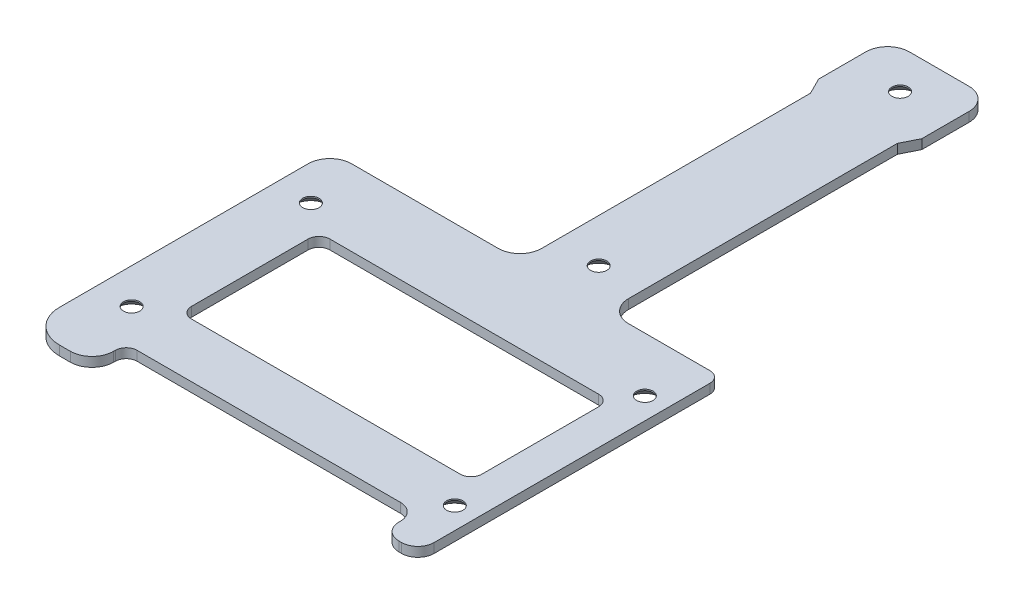
SolidWorks part; units mm, degrees
ref_plane "Front Plane" through (0, 0, 0) normal (0, 0, 1) x (1, 0, 0)
ref_plane "Top Plane" through (0, 0, 0) normal (0, 1, 0) x (1, 0, 0)
ref_plane "Right Plane" through (0, 0, 0) normal (1, 0, 0) x (0, 0, -1)
sketch "Sketch1" plane through (0, 0, 0) normal (0, 1, 0) x (1, 0, 0)
  line L0 (0, 69.2628) -> (0, -31.5647) construction
  line L1 (8, 0) -> (8, 47)
  line L2 (8, 47) -> (9.5, 50)
  line L3 (9.5, 50) -> (9.5, 58.7)
  line L4 (5.5, 62.7) -> (-5.5, 62.7)
  line L5 (20.4805, 0) -> (-4.4805, 0) construction
  line L6 (-8, 0) -> (-8, 47)
  line L7 (-8, 47) -> (-9.5, 50)
  line L8 (-9.5, 50) -> (-9.5, 58.7)
  line L9 (8, 0) -> (8, -2.5)
  line L10 (12, -6.5) -> (27, -6.5)
  line L11 (29, -8.5) -> (29, -56)
  line L12 (19.5, -56) -> (-29, -56)
  line L13 (-43, -56) -> (-43, -10.5)
  line L14 (-39, -6.5) -> (-12, -6.5)
  line L15 (-8, -2.5) -> (-8, 0)
  line L16 (-5.75, -75.9674) -> (-5.75, -4.8448) construction
  line L17 (-36.5, -8.9258) -> (-36.5, -55.9065) construction
  line L18 (25, -8.9258) -> (25, -55.9065) construction
  line L19 (-31, -22.5) -> (-31, -44)
  line L20 (22.5, -22.5) -> (22.5, -44)
  line L21 (-29, -46) -> (20.5, -46)
  line L22 (-29, -20.5) -> (20.5, -20.5)
  line L23 (-31, -58) -> (-31, -58.3)
  line L24 (22.5, -59) -> (22.5, -59.3)
  line L25 (-43, -56) -> (-43, -56.3)
  line L26 (-37, -62.3) -> (-35, -62.3)
  line L27 (25.5, -62.3) -> (26, -62.3)
  line L28 (29, -59.3) -> (29, -56)
  circle A0 centre (0, 0) radius 1.5
  circle A1 centre (0, 55.5) radius 1.5
  circle A2 centre (25, -16.5) radius 1.5
  circle A3 centre (25, -51.5) radius 1.5
  circle A4 centre (-36.5, -16.5) radius 1.5
  circle A5 centre (-36.5, -49.5) radius 1.5
  arc A6 (-43, -56.3) -> (-37, -62.3) centre (-37, -56.3) ccw
  arc A7 (-35, -62.3) -> (-31, -58.3) centre (-35, -58.3) ccw
  arc A8 (-29, -56) -> (-31, -58) centre (-29, -58) ccw
  arc A9 (26, -62.3) -> (29, -59.3) centre (26, -59.3) ccw
  arc A10 (25.5, -62.3) -> (22.5, -59.3) centre (25.5, -59.3) cw
  arc A11 (19.5, -56) -> (22.5, -59) centre (19.5, -59) cw
  arc A12 (-43, -10.5) -> (-39, -6.5) centre (-39, -10.5) cw
  arc A13 (-31, -22.5) -> (-29, -20.5) centre (-29, -22.5) cw
  arc A14 (8, -2.5) -> (12, -6.5) centre (12, -2.5) ccw
  arc A15 (-12, -6.5) -> (-8, -2.5) centre (-12, -2.5) ccw
  arc A16 (-29, -46) -> (-31, -44) centre (-29, -44) cw
  arc A17 (20.5, -46) -> (22.5, -44) centre (20.5, -44) ccw
  arc A18 (22.5, -22.5) -> (20.5, -20.5) centre (20.5, -22.5) ccw
  arc A19 (27, -6.5) -> (29, -8.5) centre (27, -8.5) cw
  arc A20 (9.5, 58.7) -> (5.5, 62.7) centre (5.5, 58.7) ccw
  arc A21 (-9.5, 58.7) -> (-5.5, 62.7) centre (-5.5, 58.7) cw
  point P18 (0, 62.7)
  point P54 (-31, -56)
  point P61 (22.5, -56)
  point P68 (8, -6.5)
  point P81 (9.5, 62.7)
  point P84 (-9.5, 62.7)
  dimension "D2" = 3
  dimension "D3" = 3
  dimension "D10" = 3
  dimension "D11" = 3
  dimension "D12" = 3
  dimension "D13" = 3
  dimension "D29" = 6
  dimension "D30" = 4
  dimension "D31" = 2
  dimension "D32" = 3
  dimension "D33" = 3
  dimension "D34" = 4
  dimension "D35" = 4
  dimension "D36" = 2
  dimension "D37" = 4
  dimension "D1" = 55.5
  dimension "D4" = 8
  dimension "D5" = 9.5
  dimension "D6" = 7.2
  dimension "D7" = 47
  dimension "D8" = 12.7
  dimension "D9" = 5.75
  dimension "D14" = 16.5
  dimension "D15" = 35
  dimension "D16" = 30.75
  dimension "D17" = 30.75
  dimension "D18" = 16.5
  dimension "D19" = 33
  dimension "D20" = 10
  dimension "D21" = 4
  dimension "D22" = 6.5
  dimension "D23" = 49.5
  dimension "D24" = 12
  dimension "D25" = 6.5
  dimension "D26" = 10
  dimension "D27" = 14
  dimension "D28" = 55.8
extrude "Boss-Extrude1" add sketch "Sketch1" along normal blind 1.75
chamfer "Chamfer1" distance 1.5 angle 45 6 edges at (25, 0, 18) (25, 0, 53) (-36.5, 0, 51) (-36.5, 0, 18) (0, 0, 1.5) (0, 0, -54)
